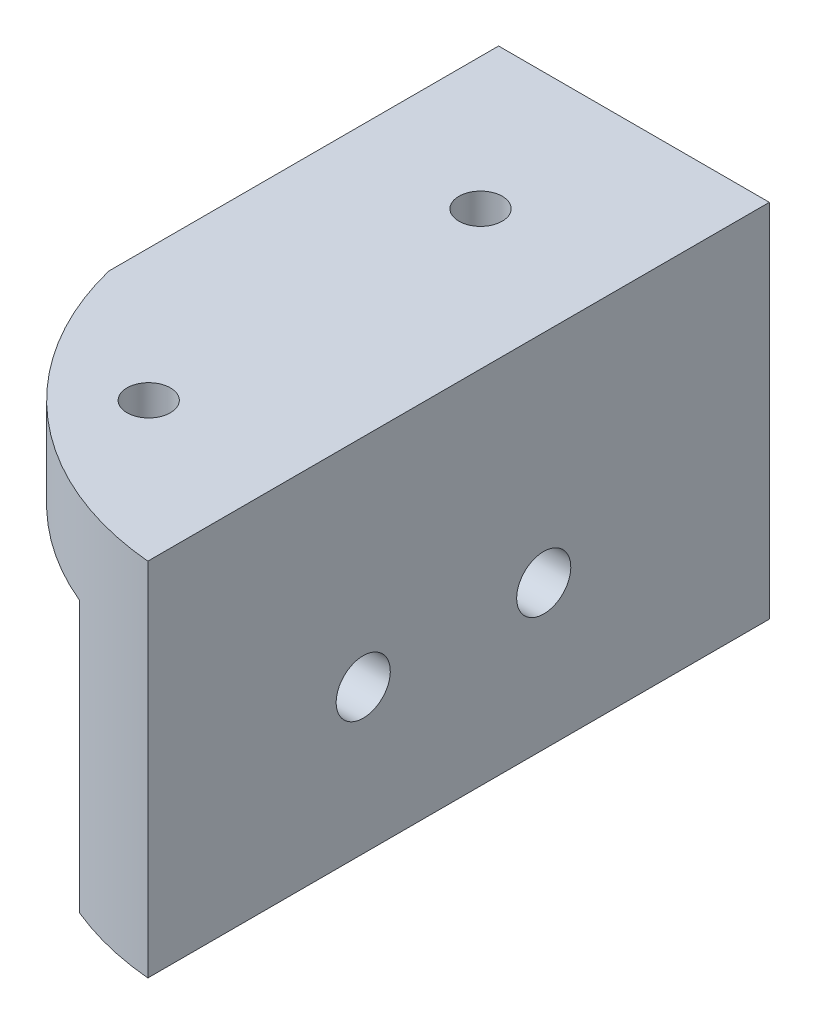
SolidWorks part; units mm, degrees
ref_plane "Front Plane" through (0, 0, 0) normal (0, 0, 1) x (1, 0, 0)
ref_plane "Top Plane" through (0, 0, 0) normal (0, 1, 0) x (1, 0, 0)
ref_plane "Right Plane" through (0, 0, 0) normal (1, 0, 0) x (0, 0, -1)
sketch "Sketch1" plane through (0, 0, 0) normal (0, 0, 1) x (1, 0, 0)
  line L0 (0, 0) -> (0, 20)
  line L1 (0, 20) -> (15, 20)
  line L2 (15, 20) -> (15, 15)
  line L3 (15, 15) -> (5, 15)
  line L4 (5, 15) -> (5, 0)
  line L5 (5, 0) -> (0, 0)
  dimension "D1" = 20
  dimension "D2" = 15
  dimension "D3" = 5
  dimension "D4" = 5
extrude "Boss-Extrude1" add sketch "Sketch1" along normal blind 35
sketch "Sketch3" plane through (0, 15, 0) normal (0, -1, 0) x (1, 0, 0)
  line L0 (7.6924, 26.6924) -> (7.6924, 8.3076) construction
  line L3 (5, 0) -> (15, 0) construction
  line L4 (5, 35) -> (15, 35) construction
  line L5 (7.6924, 8.3076) -> (-1.5, 17.5) construction
  line L6 (-1.5, 17.5) -> (7.6924, 26.6924) construction
  line L7 (0, 35) -> (0, 0) construction
  circle A0 centre (7.6924, 26.6924) radius 1.2
  circle A1 centre (7.6924, 8.3076) radius 1.2
  point P6 (7.6924, 17.5)
  point P9 (10, 0)
  dimension "D1" = 2.4
  dimension "D2" = 2.4
  dimension "D5" = 17.5
  dimension "D6" = 17.5
  dimension "D3" = 13
  dimension "D7" = 13
  dimension "D8" = 18.3848
  dimension "D4" = 1.5
extrude "Cut-Extrude1" cut sketch "Sketch3" against normal up to next
sketch "Sketch4" plane through (5, 0, 0) normal (1, 0, 0) x (0, 0, -1)
  line L0 (-22.5, 8) -> (-12.5, 8) construction
  line L1 (-35, 0) -> (-35, 15) construction
  line L2 (0, 0) -> (0, 15) construction
  line L5 (-35, 20) -> (0, 20) construction
  circle A0 centre (-22.5, 8) radius 1.5
  circle A1 centre (-12.5, 8) radius 1.5
  point P6 (-17.5, 8)
  dimension "D1" = 10
  dimension "D2" = 3
  dimension "D3" = 17.5
  dimension "D4" = 17.5
  dimension "D5" = 12
extrude "Cut-Extrude2" cut sketch "Sketch4" against normal up to next
sketch "Sketch6" plane through (0, 20, 0) normal (0, 1, 0) x (1, 0, 0)
  line L2 (-1.5, -34.5) -> (-1.5, -42.5)
  line L3 (15.5, -17.5) -> (23.5, -17.5)
  line L4 (15.5, -17.5) -> (-1.5, -17.5) construction
  line L5 (-1.5, -17.5) -> (-1.5, -34.5) construction
  circle A0 centre (-1.5, -17.5) radius 17 construction
  arc A1 (15.5, -17.5) -> (-1.5, -34.5) centre (-1.5, -17.5) cw
  arc A2 (-1.5, -42.5) -> (23.5, -17.5) centre (-1.5, -17.5) ccw
  dimension "D1" = 34
  dimension "D3" = 8
extrude "Cut-Extrude4" cut sketch "Sketch6" against normal up to next
mirror "Mirror1" about plane through (0, 0, 35) normal (1, 0, 0) of "Cut-Extrude4", "Boss-Extrude1", "Cut-Extrude1", "Cut-Extrude2"
sketch "Sketch5" plane through (0, 20, 0) normal (0, 1, 0) x (1, 0, 0)
  line L0 (15, -21.5927) -> (15, 0) construction
  line L1 (0, 0) -> (15, 0)
  line L2 (0, 0) -> (0, -35)
  line L3 (0, -35) -> (15, -35)
  line L4 (15, 0) -> (15, -35)
  dimension "D1" = 35
extrude "Cut-Extrude3" cut sketch "Sketch5" against normal up to next
equation "\"D1@Sketch3\"=\"D2@Sketch3\""
